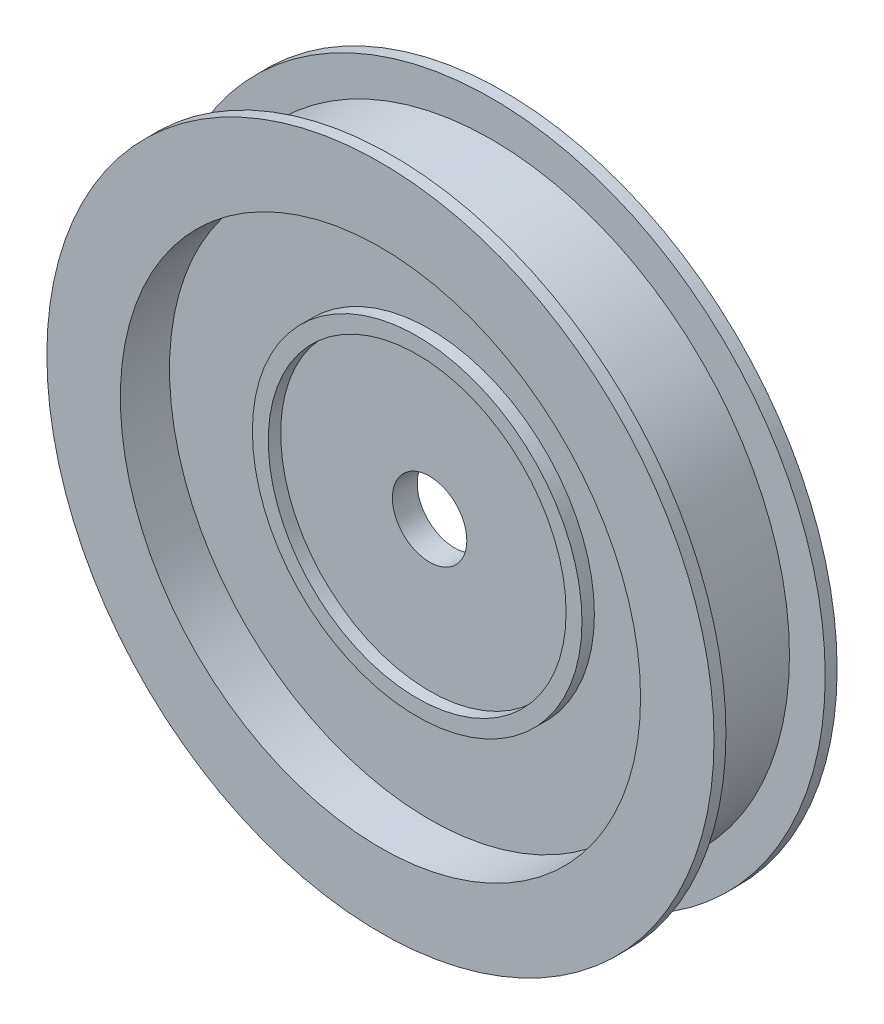
SolidWorks part; units mm, degrees
ref_plane "Front Plane" through (0, 0, 0) normal (0, 0, 1) x (1, 0, 0)
ref_plane "Top Plane" through (0, 0, 0) normal (0, 1, 0) x (1, 0, 0)
ref_plane "Right Plane" through (0, 0, 0) normal (1, 0, 0) x (0, 0, -1)
sketch "Sketch1" plane through (0, 0, 0) normal (0, 0, 1) x (1, 0, 0)
  circle A0 centre (0, 0) radius 19.05
  dimension "D1" = 38.1
extrude "Boss-Extrude1" add sketch "Sketch1" along normal mid plane 1.5875
sketch "Sketch3" plane through (0, 0, 0) normal (0, 0, 1) x (1, 0, 0)
  circle A0 centre (0, 0) radius 16.637
  circle A1 centre (0, 0) radius 19.05 construction
  circle A2 centre (0, 0) radius 19.05
  dimension "D1" = 33.274
extrude "Boss-Extrude2" add sketch "Sketch3" along normal mid plane 6.35
sketch "Sketch4" plane through (0, 0, 0) normal (0, 0, 1) x (1, 0, 0)
  circle A0 centre (0, 0) radius 9.525
  circle A1 centre (0, 0) radius 10.541
  dimension "D1" = 1.016
  dimension "D2" = 19.05
extrude "Boss-Extrude3" add sketch "Sketch4" along normal mid plane 3.175
sketch "Sketch6" plane through (0, 0, 0.7937) normal (0, 0, 1) x (1, 0, 0)
  circle A0 centre (0, 0) radius 2.3813
  dimension "D1" = 4.7625
extrude "Cut-Extrude4" cut sketch "Sketch6" against normal through all
sketch "Sketch7" plane through (0, 0, 3.175) normal (0, 0, 1) x (1, 0, 0)
  circle A0 centre (0, 0) radius 21.336
  circle A1 centre (0, 0) radius 16.637
  circle A3 centre (0, 0) radius 16.637 construction
  dimension "D1" = 42.672
extrude "Boss-Extrude5" add sketch "Sketch7" along normal blind 0.762
mirror "Mirror3" about plane through (0, 0, 0) normal (0, 0, 1) of "Boss-Extrude5"
